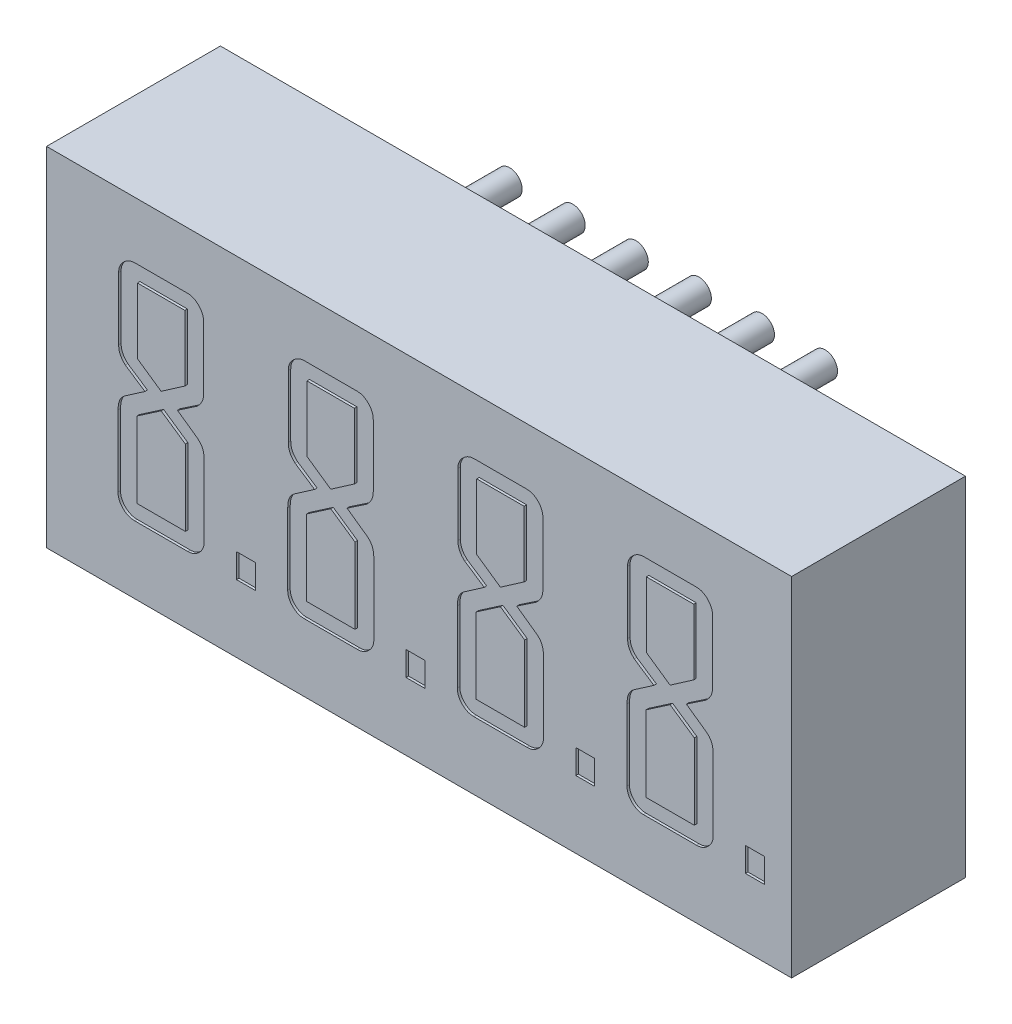
SolidWorks part; units mm, degrees
ref_plane "前视基准面" through (0, 0, 0) normal (0, 0, 1) x (1, 0, 0)
ref_plane "上视基准面" through (0, 0, 0) normal (0, 1, 0) x (1, 0, 0)
ref_plane "右视基准面" through (0, 0, 0) normal (1, 0, 0) x (0, 0, -1)
sketch "草图1" plane through (0, 0, 0) normal (0, 0, 1) x (1, 0, 0)
  line L0 (-1000, 0) -> (49000, 0) construction
  line L1 (0, -1000) -> (0, 49000) construction
  line L2 (-15, 7) -> (15, 7)
  line L3 (15, 7) -> (15, -7)
  line L4 (-15, 7) -> (-15, -7)
  line L5 (-15, -7) -> (15, -7)
  point P10 (0, 7)
  point P11 (15, 0)
  point P12 (-15, 0)
  dimension "D1" = 30
  dimension "D2" = 14
extrude "凸台-拉伸1" add sketch "草图1" along normal blind 7
sketch "草图2" plane through (0, 0, 0) normal (0, 0, -1) x (-1, 0, 0)
  line L0 (0, -1000) -> (0, 49000) construction
  line L1 (-1000, 0) -> (49000, 0) construction
  line L2 (6.35, 2.8986) -> (6.35, -3.6754) construction
  line L3 (-6.35, 2.8986) -> (-6.35, -3.6754) construction
  line L4 (-12.4563, 5.08) -> (12.3765, 5.08) construction
  line L5 (-12.4563, -5.08) -> (12.3765, -5.08) construction
  circle A0 centre (-6.35, -5.08) radius 0.5
  circle A1 centre (-3.81, -5.08) radius 0.5
  circle A2 centre (-1.27, -5.08) radius 0.5
  circle A3 centre (1.27, -5.08) radius 0.5
  circle A4 centre (3.81, -5.08) radius 0.5
  circle A5 centre (6.35, -5.08) radius 0.5
  circle A6 centre (-6.35, 5.08) radius 0.5
  circle A7 centre (-3.81, 5.08) radius 0.5
  circle A8 centre (-1.27, 5.08) radius 0.5
  circle A9 centre (1.27, 5.08) radius 0.5
  circle A10 centre (3.81, 5.08) radius 0.5
  circle A11 centre (6.35, 5.08) radius 0.5
  dimension "D3" = 6
  dimension "D1" = 12.7
  dimension "D2" = 10.16
  dimension "D4" = 2
extrude "凸台-拉伸2" add sketch "草图2" along normal blind 3
sketch "草图3" plane through (0, 0, 7) normal (0, 0, 1) x (1, 0, 0)
  text T0 "8.8.8.8." font "Agency FB" height 9
extrude "切除-拉伸1" cut sketch "草图3" against normal blind 0.1
